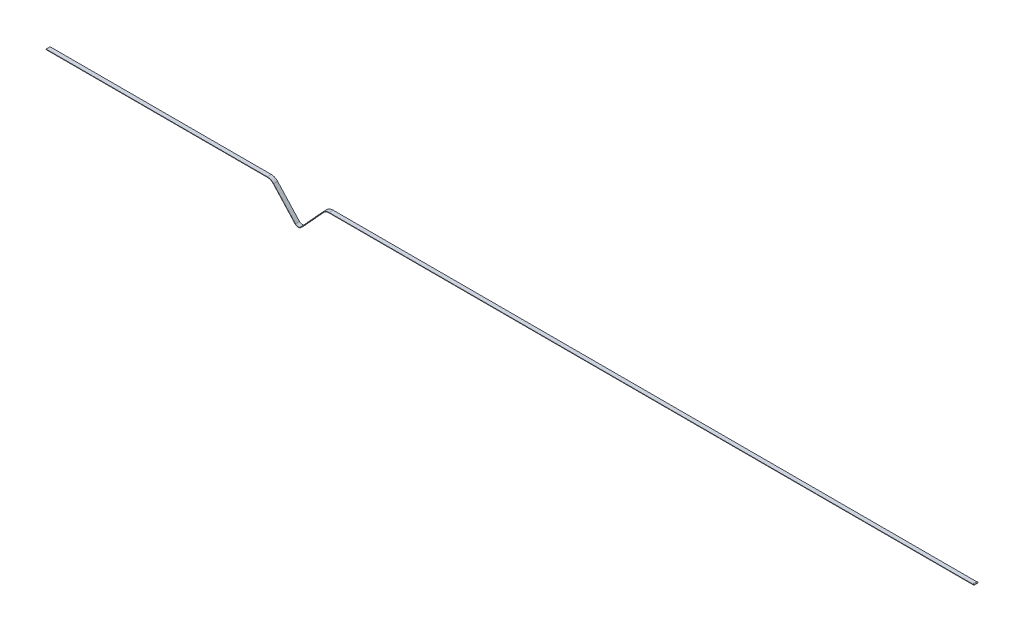
SolidWorks part; units mm, degrees
material "BUTYL"
ref_plane "Front Plane" through (0, 0, 0) normal (0, 0, 1) x (1, 0, 0)
ref_plane "Top Plane" through (0, 0, 0) normal (0, 1, 0) x (1, 0, 0)
ref_plane "Right Plane" through (0, 0, 0) normal (1, 0, 0) x (0, 0, -1)
sketch "Sketch1" plane through (0, 0, 0) normal (1, 0, 0) x (0, 0, -1)
  line L1 (0, 0) -> (6, 0)
  line L2 (0, 0) -> (0, 0.63)
  line L3 (0, 0.63) -> (6, 0.63)
  line L4 (6, 0) -> (6, 0.63)
  dimension "D1" = 0.63
  dimension "D2" = 6
sketch "Sketch2" plane through (0, 0, 0) normal (0, 0, 1) x (1, 0, 0)
  line L0 (0, 0) -> (-953.346, 0)
  line L1 (-962.165, -3.886) -> (-994.4069, -39.1468)
  line L2 (-1003.4251, -39.1468) -> (-1035.667, -3.886)
  line L3 (-1044.486, 0) -> (-1371.6, 0)
  arc A0 (-953.346, 0) -> (-962.165, -3.886) centre (-953.346, -11.95) ccw
  arc A1 (-994.4069, -39.1468) -> (-1003.4251, -39.1468) centre (-998.916, -35.0237) cw
  arc A2 (-1035.667, -3.886) -> (-1044.486, 0) centre (-1044.486, -11.95) ccw
  circle A3 centre (-953.346, -11.95) radius 11.95 construction
  circle A4 centre (-1044.486, -11.95) radius 11.95 construction
  circle A5 centre (-998.916, -35.0237) radius 6.11 construction
  dimension "D1" = 6.11
  dimension "D4" = 1371.6
sweep "Sweep1" add profiles "Sketch1" path "Sketch2"
sketch "Sketch3" plane through (0, 0, 0) normal (0, 0, 1) x (1, 0, 0)
  line L0 (0, 0.63) -> (-953.346, 0.63) construction
  line L1 (-1.5, 0.63) -> (-1.5, 0)
  line L2 (0, 0) -> (-953.346, 0) construction
  line L3 (-1.5, 0) -> (0, 0)
  line L4 (0, 0) -> (0, 0.63)
  arc A1 (0, 0.63) -> (-1.5, 0.63) centre (-0.75, 0.63) ccw
  dimension "D1" = 0.75
extrude "Boss-Extrude1" add sketch "Sketch3" against normal through all
pattern_curve "CrvPattern1" [suppressed] parameters "D1"=2000, "D3"=2, "D2"=1, "D4"=10
